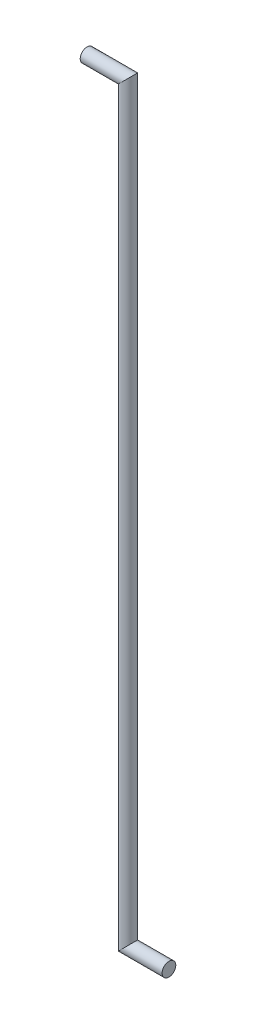
SolidWorks part; units mm, degrees
ref_plane "Front Plane" through (0, 0, 0) normal (0, 0, 1) x (1, 0, 0)
ref_plane "Top Plane" through (0, 0, 0) normal (0, 1, 0) x (1, 0, 0)
ref_plane "Right Plane" through (0, 0, 0) normal (1, 0, 0) x (0, 0, -1)
sketch "Sketch1" plane through (0, 0, 0) normal (0, 0, 1) x (1, 0, 0)
  line L0 (-3, 27.5) -> (0, 27.5)
  line L1 (0, 27.5) -> (0, -27.5)
  line L2 (0, -27.5) -> (3, -27.5)
  point P5 (0, 0)
  dimension "D1" = 3
  dimension "D2" = 55
sweep "Sweep1" add path "Sketch1" circular profile diameter 1 parameters "D3"=1
